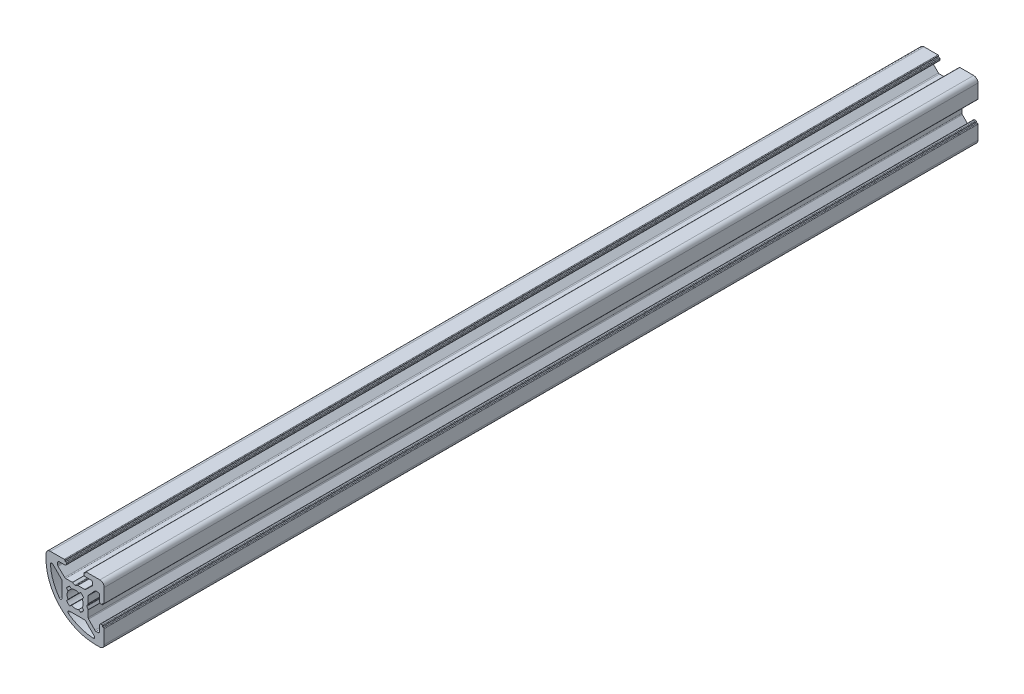
SolidWorks part; units mm, degrees
ref_plane "Front Plane" through (0, 0, 0) normal (0, 0, 1) x (1, 0, 0)
ref_plane "Top Plane" through (0, 0, 0) normal (0, 1, 0) x (1, 0, 0)
ref_plane "Right Plane" through (0, 0, 0) normal (1, 0, 0) x (0, 0, -1)
sketch "Sketch1" plane through (0, 0, 0) normal (0, 0, 1) x (1, 0, 0)
  line L0 (1.2582, 2.4453) -> (1.8871, 2.9477)
  line L1 (1.2582, -2.4453) -> (1.8871, -2.9477)
  line L2 (3.2322, 4.5654) -> (0.9536, 4.5654)
  line L3 (3.2322, -4.5) -> (-2, -4.5)
  line L4 (-1.2582, -2.4453) -> (-1.8871, -2.9477)
  line L5 (-4.6464, 3.5858) -> (-7.6257, 6.565)
  line L6 (-10, 7) -> (-10, 8.5)
  line L7 (-2.4453, -1.2582) -> (-2.9477, -1.8871)
  line L8 (-2.4453, 1.2582) -> (-2.9477, 1.8871)
  line L9 (-4.5, 3.2322) -> (-4.5, -2)
  line L10 (-1.2582, 2.4453) -> (-1.8871, 2.9477)
  line L11 (-3.2322, 4.5654) -> (-0.9536, 4.5654)
  line L12 (-3.2, 9.45) -> (-3.35, 9.45)
  line L13 (-3, 8.9321) -> (-3, 9.25)
  line L14 (-3.4918, 8.4403) -> (-5.5082, 8.4403)
  line L15 (-3.5763, 4.7027) -> (-5.8441, 6.8535)
  line L16 (-6, 7.2162) -> (-6, 7.9485)
  line L17 (-0.8536, 4.5387) -> (-0.1, 4.1036)
  line L18 (0.8536, 4.5387) -> (0.1, 4.1036)
  line L19 (-3.75, 10) -> (-8.5, 10)
  line L20 (-3.55, 9.65) -> (-3.55, 9.8)
  line L21 (4.5, -3.2322) -> (4.5, -0.9536)
  line L22 (9.65, -3.55) -> (9.8, -3.55)
  line L23 (7, -10) -> (8.5, -10)
  line L24 (4.6372, -3.5763) -> (6.788, -5.8441)
  line L25 (3.5858, -4.6464) -> (6.565, -7.6257)
  line L26 (8.3748, -3.4918) -> (8.3748, -5.5082)
  line L27 (9.45, -3.2) -> (9.45, -3.35)
  line L28 (8.8666, -3) -> (9.25, -3)
  line L29 (7.1508, -6) -> (7.883, -6)
  line L30 (10, -3.75) -> (10, -8.5)
  line L31 (9.65, 3.55) -> (9.8, 3.55)
  line L32 (8.3748, 3.4918) -> (8.3748, 5.5082)
  line L33 (4.6372, 3.5763) -> (6.788, 5.8441)
  line L34 (2.4453, 1.2582) -> (2.9477, 1.8871)
  line L35 (2.4453, -1.2582) -> (2.9477, -1.8871)
  line L36 (4.5, 3.2322) -> (4.5, 0.9536)
  line L37 (4.4732, 0.8536) -> (4.0381, 0.1)
  line L38 (4.4732, -0.8536) -> (4.0381, -0.1)
  line L39 (9.45, 3.2) -> (9.45, 3.35)
  line L40 (8.8666, 3) -> (9.25, 3)
  line L42 (3.5763, 4.7027) -> (5.8441, 6.8535)
  line L43 (3.4918, 8.4403) -> (5.5082, 8.4403)
  line L44 (3.2, 9.45) -> (3.35, 9.45)
  line L45 (3, 8.9321) -> (3, 9.25)
  line L46 (6, 7.2162) -> (6, 7.9485)
  line L47 (7.1508, 6) -> (7.883, 6)
  line L48 (10, 3.75) -> (10, 8.5)
  line L49 (3.75, 10) -> (8.5, 10)
  line L50 (3.55, 9.65) -> (3.55, 9.8)
  line L51 (0, 13.6082) -> (0, -13.4183) construction
  line L52 (-13.988, 0) -> (15.7602, 0) construction
  arc A0 (-2.3, -5.4) -> (6.1852, -8.4786) centre (7, 7) ccw
  arc A1 (-10, 7) -> (7, -10) centre (7, 7) ccw
  arc A2 (-3.55, 9.65) -> (-3.35, 9.45) centre (-3.35, 9.65) ccw
  arc A3 (-8.5, 10) -> (-10, 8.5) centre (-8.5, 8.5) ccw
  arc A4 (-5.4, -2.3) -> (-4.5, -2) centre (-5, -2) ccw
  arc A5 (-8.4786, 6.1852) -> (-5.4, -2.3) centre (7, 7) ccw
  arc A6 (-2.9477, -1.8871) -> (-1.8871, -2.9477) centre (0, 0) ccw
  arc A7 (-2, -4.5) -> (-2.3, -5.4) centre (-2, -5) ccw
  arc A8 (-1.2582, -2.4453) -> (1.2582, -2.4453) centre (0, 0) ccw
  arc A9 (-7.6257, 6.565) -> (-8.4786, 6.1852) centre (-7.9793, 6.2115) ccw
  arc A10 (-1.8871, 2.9477) -> (-2.9477, 1.8871) centre (0, 0) ccw
  arc A11 (-4.5, 3.2322) -> (-4.6464, 3.5858) centre (-5, 3.2322) ccw
  arc A12 (1.2582, 2.4453) -> (-1.2582, 2.4453) centre (0, 0) ccw
  arc A13 (-2.4453, 1.2582) -> (-2.4453, -1.2582) centre (0, 0) ccw
  arc A14 (-3, 9.25) -> (-3.2, 9.45) centre (-3.2, 9.25) ccw
  arc A15 (-3.4918, 8.4403) -> (-3, 8.9321) centre (-3.4918, 8.9321) ccw
  arc A16 (-3.5763, 4.7027) -> (-3.2322, 4.5654) centre (-3.2322, 5.0654) ccw
  arc A17 (-6, 7.2162) -> (-5.8441, 6.8535) centre (-5.5, 7.2162) ccw
  arc A18 (-5.5082, 8.4403) -> (-6, 7.9485) centre (-5.5082, 7.9485) ccw
  arc A19 (-0.1, 4.1036) -> (0.1, 4.1036) centre (0, 4.2768) ccw
  arc A20 (0.9536, 4.5654) -> (0.8536, 4.5387) centre (0.9536, 4.3654) ccw
  arc A21 (-0.8536, 4.5387) -> (-0.9536, 4.5654) centre (-0.9536, 4.3654) ccw
  arc A22 (-3.55, 9.8) -> (-3.75, 10) centre (-3.75, 9.8) ccw
  arc A23 (3.35, 9.45) -> (3.55, 9.65) centre (3.35, 9.65) ccw
  arc A24 (10, 8.5) -> (8.5, 10) centre (8.5, 8.5) ccw
  arc A25 (1.8871, -2.9477) -> (2.9477, -1.8871) centre (0, 0) ccw
  arc A26 (8.5, -10) -> (10, -8.5) centre (8.5, -8.5) ccw
  arc A27 (6.1852, -8.4786) -> (6.565, -7.6257) centre (6.2115, -7.9793) ccw
  arc A28 (4.5, -3.2322) -> (4.6372, -3.5763) centre (5, -3.2322) ccw
  arc A29 (3.5858, -4.6464) -> (3.2322, -4.5) centre (3.2322, -5) ccw
  arc A30 (9.45, -3.2) -> (9.25, -3) centre (9.25, -3.2) ccw
  arc A31 (9.45, -3.35) -> (9.65, -3.55) centre (9.65, -3.35) ccw
  arc A32 (8.8666, -3) -> (8.3748, -3.4918) centre (8.8666, -3.4918) ccw
  arc A33 (6.788, -5.8441) -> (7.1508, -6) centre (7.1508, -5.5) ccw
  arc A34 (7.883, -6) -> (8.3748, -5.5082) centre (7.883, -5.5082) ccw
  arc A35 (10, -3.75) -> (9.8, -3.55) centre (9.8, -3.75) ccw
  arc A36 (2.4453, -1.2582) -> (2.4453, 1.2582) centre (0, 0) ccw
  arc A37 (2.9477, 1.8871) -> (1.8871, 2.9477) centre (0, 0) ccw
  arc A38 (4.0381, 0.1) -> (4.0381, -0.1) centre (4.2113, 0) ccw
  arc A39 (4.5, -0.9536) -> (4.4732, -0.8536) centre (4.3, -0.9536) ccw
  arc A40 (4.4732, 0.8536) -> (4.5, 0.9536) centre (4.3, 0.9536) ccw
  arc A41 (4.6372, 3.5763) -> (4.5, 3.2322) centre (5, 3.2322) ccw
  arc A42 (9.65, 3.55) -> (9.45, 3.35) centre (9.65, 3.35) ccw
  arc A43 (9.25, 3) -> (9.45, 3.2) centre (9.25, 3.2) ccw
  arc A44 (8.3748, 3.4918) -> (8.8666, 3) centre (8.8666, 3.4918) ccw
  arc A45 (6, 7.9485) -> (5.5082, 8.4403) centre (5.5082, 7.9485) ccw
  arc A46 (3.2, 9.45) -> (3, 9.25) centre (3.2, 9.25) ccw
  arc A47 (3, 8.9321) -> (3.4918, 8.4403) centre (3.4918, 8.9321) ccw
  arc A48 (3.2322, 4.5654) -> (3.5763, 4.7027) centre (3.2322, 5.0654) ccw
  arc A49 (5.8441, 6.8535) -> (6, 7.2162) centre (5.5, 7.2162) ccw
  arc A50 (7.1508, 6) -> (6.788, 5.8441) centre (7.1508, 5.5) ccw
  arc A51 (8.3748, 5.5082) -> (7.883, 6) centre (7.883, 5.5082) ccw
  arc A52 (9.8, 3.55) -> (10, 3.75) centre (9.8, 3.75) ccw
  arc A53 (3.75, 10) -> (3.55, 9.8) centre (3.75, 9.8) ccw
  dimension "D1" = 5.5
  dimension "D5" = 17
  dimension "D7" = 5.5
  dimension "D8" = 12
  dimension "D2" = 20
  dimension "D3" = 20
  dimension "D4" = 10
  dimension "D6" = 6
  dimension "D9" = 12
extrude "Extrude1" add sketch "Sketch1" along normal blind 300
